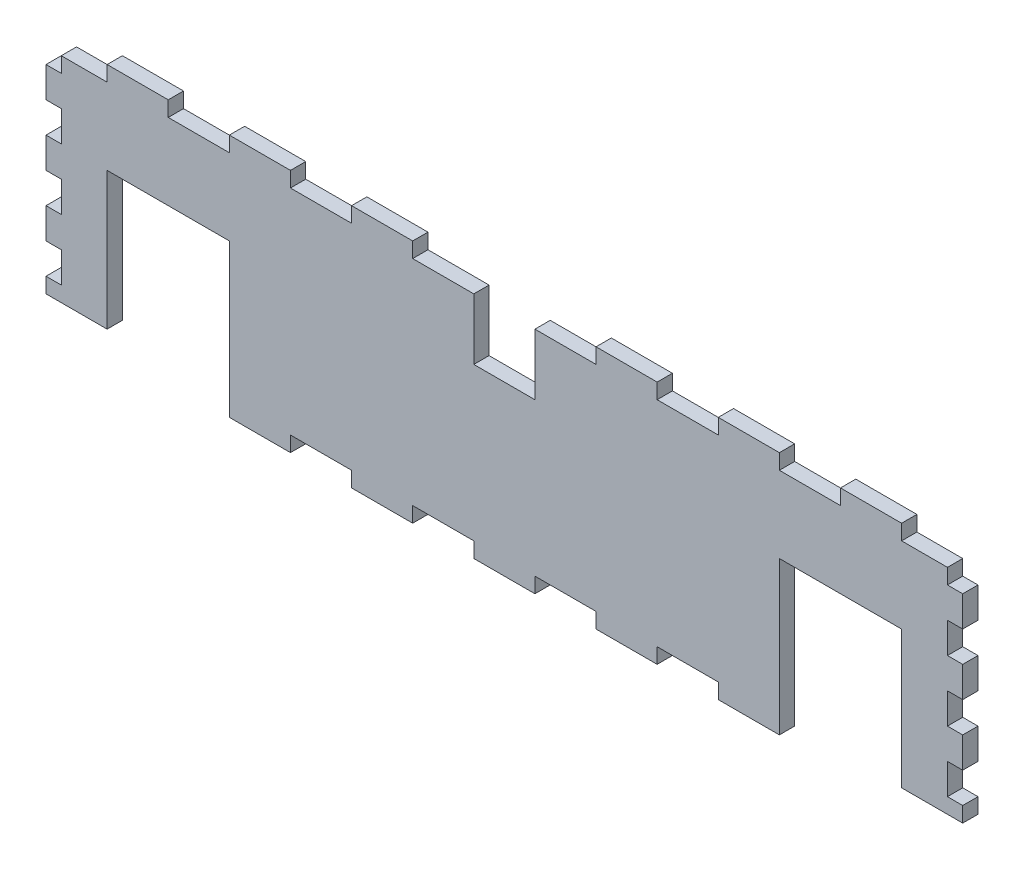
SolidWorks part; units mm, degrees
ref_plane "Front Plane" through (0, 0, 0) normal (0, 0, 1) x (1, 0, 0)
ref_plane "Top Plane" through (0, 0, 0) normal (0, 1, 0) x (1, 0, 0)
ref_plane "Right Plane" through (0, 0, 0) normal (1, 0, 0) x (0, 0, -1)
sketch "Sketch1" plane through (0, 0, 0) normal (0, 0, 1) x (1, 0, 0)
  line L1 (-190.5, -50.8) -> (190.5, -50.8)
  line L2 (-190.5, -50.8) -> (-190.5, 50.8)
  line L3 (-190.5, 50.8) -> (190.5, 50.8)
  line L4 (190.5, -50.8) -> (190.5, 50.8)
  line L5 (-190.5, -50.8) -> (190.5, 50.8) construction
  line L6 (-190.5, 50.8) -> (190.5, -50.8) construction
  point P0 (0, 0)
  dimension "D1" = 381
  dimension "D2" = 101.6
extrude "Boss-Extrude1" add sketch "Sketch1" along normal blind 6.35
sketch "Sketch2" plane through (0, 0, 6.35) normal (0, 0, 1) x (1, 0, 0)
  line L0 (-139.7, 50.8) -> (-139.7, 44.45)
  line L1 (-190.5, 50.8) -> (-165.1, 50.8)
  line L2 (-190.5, 50.8) -> (-190.5, 44.45)
  line L3 (-190.5, 44.45) -> (-165.1, 44.45)
  line L4 (-165.1, 50.8) -> (-165.1, 44.45)
  line L5 (-139.7, 50.8) -> (-114.3, 50.8)
  line L6 (-114.3, 50.8) -> (-114.3, 44.45)
  line L7 (-139.7, 44.45) -> (-114.3, 44.45)
  line L8 (-88.9, 50.8) -> (-88.9, 44.45)
  line L9 (-88.9, 50.8) -> (-63.5, 50.8)
  line L10 (-63.5, 50.8) -> (-63.5, 44.45)
  line L11 (-88.9, 44.45) -> (-63.5, 44.45)
  line L12 (-38.1, 50.8) -> (-38.1, 44.45)
  line L13 (-38.1, 50.8) -> (-12.7, 50.8)
  line L14 (-12.7, 50.8) -> (-12.7, 44.45)
  line L15 (-38.1, 44.45) -> (-12.7, 44.45)
  line L16 (12.7, 50.8) -> (12.7, 44.45)
  line L17 (12.7, 50.8) -> (38.1, 50.8)
  line L18 (38.1, 50.8) -> (38.1, 44.45)
  line L19 (12.7, 44.45) -> (38.1, 44.45)
  line L20 (63.5, 50.8) -> (63.5, 44.45)
  line L21 (63.5, 50.8) -> (88.9, 50.8)
  line L22 (88.9, 50.8) -> (88.9, 44.45)
  line L23 (63.5, 44.45) -> (88.9, 44.45)
  line L24 (114.3, 50.8) -> (114.3, 44.45)
  line L25 (114.3, 50.8) -> (139.7, 50.8)
  line L26 (139.7, 50.8) -> (139.7, 44.45)
  line L27 (114.3, 44.45) -> (139.7, 44.45)
  line L28 (165.1, 50.8) -> (165.1, 44.45)
  line L29 (165.1, 50.8) -> (190.5, 50.8)
  line L30 (190.5, 50.8) -> (190.5, 44.45)
  line L31 (165.1, 44.45) -> (190.5, 44.45)
  line L32 (0, 0) -> (17.1366, 0)
  line L33 (0, 0) -> (0, 20.0911)
  line L34 (165.1, -50.8) -> (190.5, -50.8)
  line L35 (190.5, -50.8) -> (190.5, -44.45)
  line L36 (165.1, -44.45) -> (190.5, -44.45)
  line L37 (165.1, -50.8) -> (165.1, -44.45)
  line L38 (114.3, -50.8) -> (139.7, -50.8)
  line L39 (139.7, -50.8) -> (139.7, -44.45)
  line L40 (114.3, -44.45) -> (139.7, -44.45)
  line L41 (114.3, -50.8) -> (114.3, -44.45)
  line L42 (63.5, -50.8) -> (88.9, -50.8)
  line L43 (88.9, -50.8) -> (88.9, -44.45)
  line L44 (63.5, -44.45) -> (88.9, -44.45)
  line L45 (63.5, -50.8) -> (63.5, -44.45)
  line L46 (12.7, -50.8) -> (38.1, -50.8)
  line L47 (38.1, -50.8) -> (38.1, -44.45)
  line L48 (12.7, -44.45) -> (38.1, -44.45)
  line L49 (12.7, -50.8) -> (12.7, -44.45)
  line L50 (-38.1, -50.8) -> (-12.7, -50.8)
  line L51 (-12.7, -50.8) -> (-12.7, -44.45)
  line L52 (-38.1, -44.45) -> (-12.7, -44.45)
  line L53 (-38.1, -50.8) -> (-38.1, -44.45)
  line L54 (-88.9, -50.8) -> (-63.5, -50.8)
  line L55 (-63.5, -50.8) -> (-63.5, -44.45)
  line L56 (-88.9, -44.45) -> (-63.5, -44.45)
  line L57 (-88.9, -50.8) -> (-88.9, -44.45)
  line L58 (-139.7, -50.8) -> (-114.3, -50.8)
  line L59 (-114.3, -50.8) -> (-114.3, -44.45)
  line L60 (-139.7, -44.45) -> (-114.3, -44.45)
  line L61 (-139.7, -50.8) -> (-139.7, -44.45)
  line L62 (-190.5, -44.45) -> (-165.1, -44.45)
  line L63 (-165.1, -50.8) -> (-165.1, -44.45)
  line L64 (-190.5, -50.8) -> (-165.1, -50.8)
  line L65 (-190.5, -50.8) -> (-190.5, -44.45)
  line L66 (-190.5, 25.4) -> (-190.5, 12.7)
  line L67 (-190.5, 50.8) -> (-184.15, 50.8)
  line L68 (-190.5, 50.8) -> (-190.5, 38.1)
  line L69 (-190.5, 38.1) -> (-184.15, 38.1)
  line L70 (-184.15, 50.8) -> (-184.15, 38.1)
  line L71 (-190.5, 25.4) -> (-184.15, 25.4)
  line L72 (-184.15, 25.4) -> (-184.15, 12.7)
  line L73 (-190.5, 12.7) -> (-184.15, 12.7)
  line L74 (-190.5, 0) -> (-190.5, -12.7)
  line L75 (-190.5, 0) -> (-184.15, 0)
  line L76 (-184.15, 0) -> (-184.15, -12.7)
  line L77 (-190.5, -12.7) -> (-184.15, -12.7)
  line L78 (-190.5, -25.4) -> (-190.5, -38.1)
  line L79 (-190.5, -25.4) -> (-184.15, -25.4)
  line L80 (-184.15, -25.4) -> (-184.15, -38.1)
  line L81 (-190.5, -38.1) -> (-184.15, -38.1)
  line L83 (190.5, -25.4) -> (184.15, -25.4)
  line L84 (184.15, -25.4) -> (184.15, -38.1)
  line L85 (190.5, -38.1) -> (184.15, -38.1)
  line L86 (190.5, -25.4) -> (190.5, -38.1)
  line L87 (190.5, 0) -> (184.15, 0)
  line L88 (184.15, 0) -> (184.15, -12.7)
  line L89 (190.5, -12.7) -> (184.15, -12.7)
  line L90 (190.5, 0) -> (190.5, -12.7)
  line L91 (190.5, 25.4) -> (184.15, 25.4)
  line L92 (184.15, 25.4) -> (184.15, 12.7)
  line L93 (190.5, 12.7) -> (184.15, 12.7)
  line L94 (190.5, 25.4) -> (190.5, 12.7)
  line L95 (190.5, 38.1) -> (184.15, 38.1)
  line L96 (184.15, 50.8) -> (184.15, 38.1)
  line L97 (190.5, 50.8) -> (184.15, 50.8)
  line L98 (190.5, 50.8) -> (190.5, 38.1)
  line M51 (190.5, -50.8) -> (190.5, 50.8)
  line M52 (190.5, 50.8) -> (-190.5, 50.8)
  line M53 (-190.5, 50.8) -> (-190.5, -50.8)
  line M54 (-190.5, -50.8) -> (190.5, -50.8)
  dimension "D1" = 25.4
  dimension "D2" = 6.35
  dimension "D4" = 6.35
  dimension "D5" = 12.7
  dimension "D3" = 8
  dimension "D6" = 4
extrude "Cut-Extrude1" cut sketch "Sketch2" against normal blind 6.35 contours L70 L3 L4 M52 | L70 L1 L3 M53 | L70 L3 L69 M53 | L73 L72 L71 M53 | L77 L76 L75 M53 | L81 L80 L79 M53 | L63 L62 M54 M53 | L61 L59 L60 M54 | L57 L55 L56 M54 | L53 L51 L52 M54 | L49 L47 L48 M54 | L0 L7 L6 M52 | L8 L11 L10 M52 | L12 L15 L14 M52 | L16 L19 L18 M52 | L20 L23 L22 M52 | L45 L43 L44 M54 | L41 L39 L40 M54 | L24 L27 L26 M52 | L96 L29 L28 L31 | L96 L31 M52 M51 | L31 L96 L95 M51 | L93 L91 L92 M51 | L89 L87 L88 M51 | L85 L83 L84 M51 | L37 L36 M54 M51
sketch "Sketch3" plane through (0, 0, 6.35) normal (0, 0, 1) x (1, 0, 0)
  line L0 (-114.3, 50.8) -> (-114.3, 44.45) construction
  line L1 (-165.1, 50.8) -> (-114.3, 50.8)
  line L2 (-165.1, 50.8) -> (-165.1, 12.7)
  line L3 (-165.1, 12.7) -> (-114.3, 12.7)
  line L4 (-114.3, 50.8) -> (-114.3, 12.7)
  line L5 (0, 0) -> (0, 16.8168)
  line L6 (-165.1, 12.7) -> (-114.3, 12.7)
  line L7 (-165.1, 12.7) -> (-165.1, -50.8)
  line L8 (-165.1, -50.8) -> (-114.3, -50.8)
  line L9 (-114.3, 12.7) -> (-114.3, -50.8)
  line L10 (165.1, -50.8) -> (114.3, -50.8)
  line L11 (114.3, 12.7) -> (114.3, -50.8)
  line L12 (165.1, 12.7) -> (114.3, 12.7)
  line L13 (165.1, 12.7) -> (165.1, -50.8)
  dimension "D1" = 38.1
extrude "Cut-Extrude2" cut sketch "Sketch3" against normal blind 6.35 contours L9 L3 L7 L8 | L13 L12 L11 L10
sketch "Sketch4" plane through (0, 0, 6.35) normal (0, 0, 1) x (1, 0, 0)
  line L0 (12.7, 50.8) -> (12.7, 44.45) construction
  line L1 (-12.7, 50.8) -> (12.7, 50.8)
  line L2 (-12.7, 50.8) -> (-12.7, 19.05)
  line L3 (-12.7, 19.05) -> (12.7, 19.05)
  line L4 (12.7, 50.8) -> (12.7, 19.05)
  dimension "D1" = 31.75
extrude "Cut-Extrude3" cut sketch "Sketch4" against normal blind 6.35
